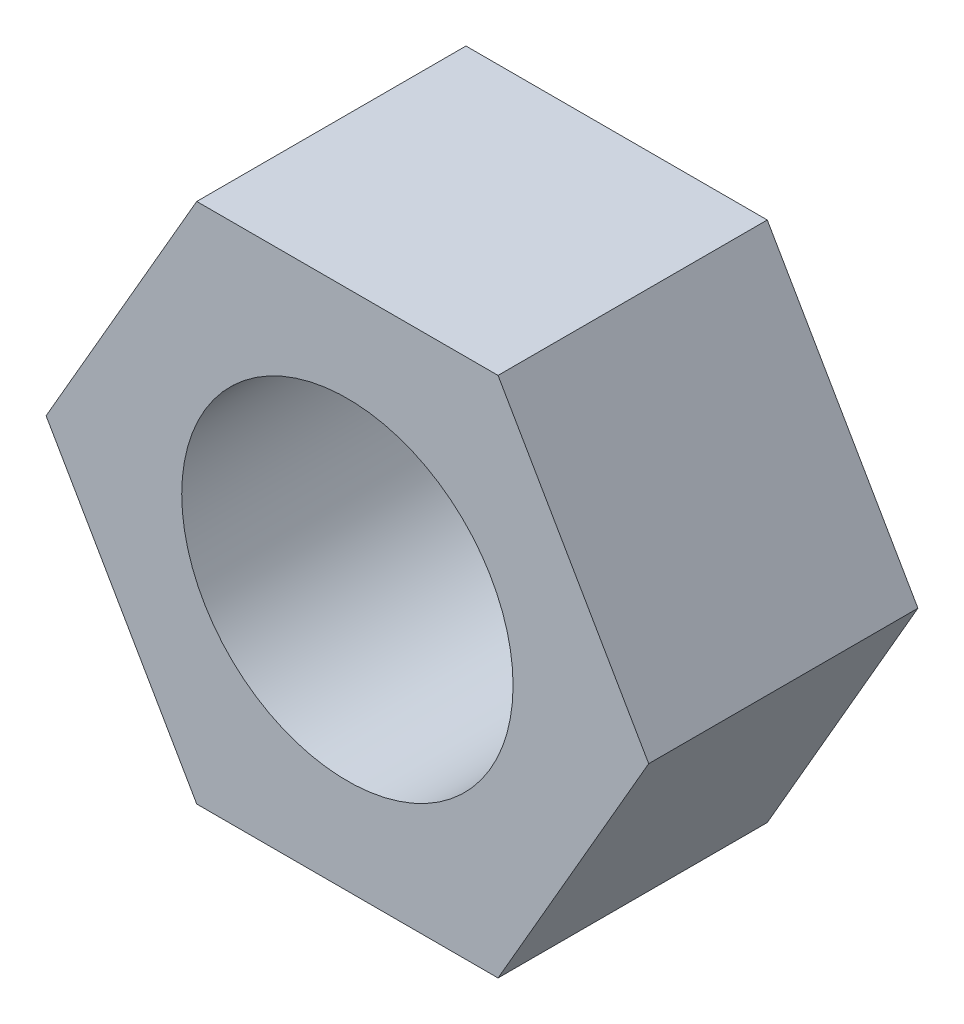
SolidWorks part; units mm, degrees
ref_plane "Front Plane" through (0, 0, 0) normal (0, 0, 1) x (1, 0, 0)
ref_plane "Top Plane" through (0, 0, 0) normal (0, 1, 0) x (1, 0, 0)
ref_plane "Right Plane" through (0, 0, 0) normal (1, 0, 0) x (0, 0, -1)
sketch "Sketch1" plane through (0, 0, 0) normal (0, 0, 1) x (1, 0, 0)
  line L1 (7.2746, 260) -> (3.6373, 266.3)
  line L2 (3.6373, 266.3) -> (-3.6373, 266.3)
  line L3 (-3.6373, 266.3) -> (-7.2746, 260)
  line L4 (-7.2746, 260) -> (-3.6373, 253.7)
  line L5 (-3.6373, 253.7) -> (3.6373, 253.7)
  line L6 (3.6373, 253.7) -> (7.2746, 260)
  circle A0 centre (0, 260) radius 6.3 construction
  circle A1 centre (0, 260) radius 4
  dimension "D2" = 8
  dimension "D1" = 12.6
extrude "Boss-Extrude1" add sketch "Sketch1" along normal blind 6.5
